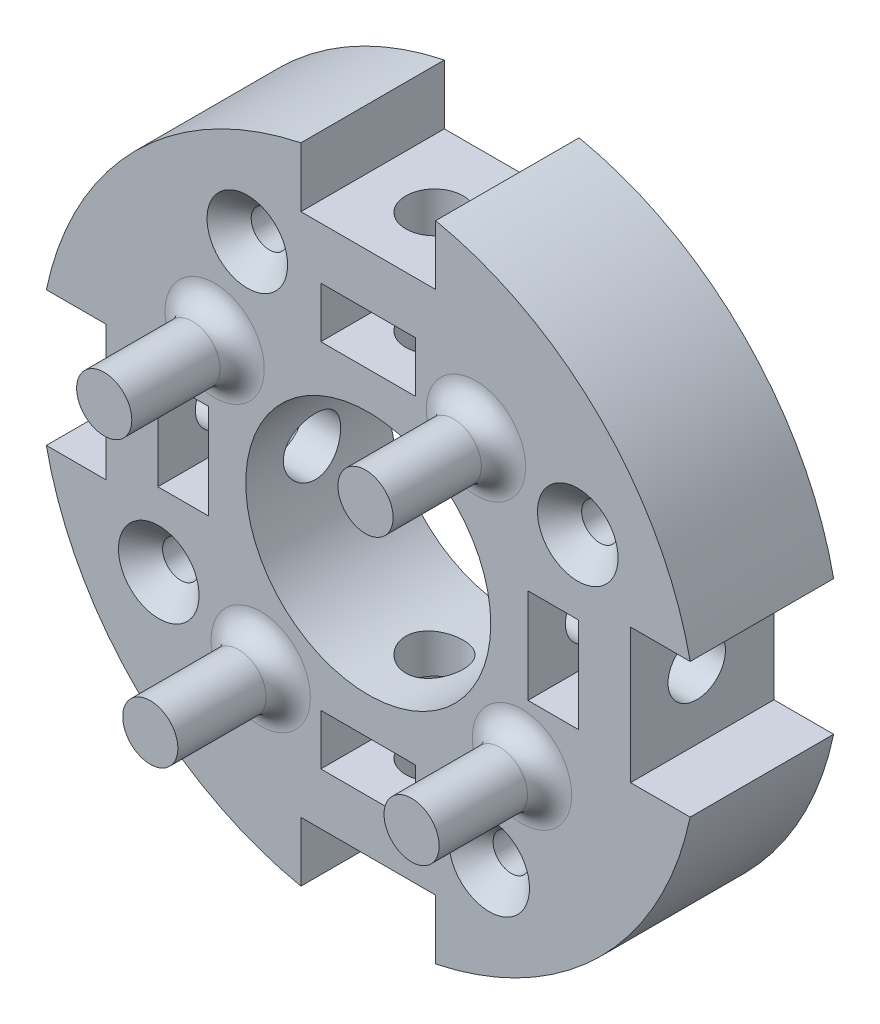
SolidWorks part; units mm, degrees
ref_plane "Plan de face" through (0, 0, 0) normal (0, 0, 1) x (1, 0, 0)
ref_plane "Plan de dessus" through (0, 0, 0) normal (0, 1, 0) x (1, 0, 0)
ref_plane "Plan de droite" through (0, 0, 0) normal (1, 0, 0) x (0, 0, -1)
sketch "Esquisse1" plane through (0, 0, 0) normal (0, 0, 1) x (1, 0, 0)
  line L1 (-29.4129, -5.9059) -> (-23.9629, -5.9059) construction
  line L3 (-29.4129, 5.9059) -> (-23.9629, 5.9059) construction
  line L4 (-23.9629, -5.9059) -> (-23.9629, 5.9059) construction
  line L5 (-29.4129, -5.9059) -> (-23.9629, 5.9059) construction
  line L6 (-29.4129, 5.9059) -> (-23.9629, -5.9059) construction
  line L7 (-5.9059, 29.4129) -> (-5.9059, 23.9629) construction
  line L8 (-5.9059, 23.9629) -> (5.9059, 23.9629) construction
  line L9 (5.9059, 29.4129) -> (5.9059, 23.9629) construction
  line L11 (29.4129, 5.9059) -> (23.9629, 5.9059) construction
  line L12 (23.9629, 5.9059) -> (23.9629, -5.9059) construction
  line L13 (29.4129, -5.9059) -> (23.9629, -5.9059) construction
  line L15 (5.9059, -29.4129) -> (5.9059, -23.9629) construction
  line L16 (5.9059, -23.9629) -> (-5.9059, -23.9629) construction
  line L17 (-5.9059, -29.4129) -> (-5.9059, -23.9629) construction
  line L18 (-6.1059, 29.1677) -> (-6.1059, 23.7629)
  line L19 (-6.1059, 23.7629) -> (6.1059, 23.7629)
  line L20 (6.1059, 29.1677) -> (6.1059, 23.7629)
  line L21 (29.1677, 6.1059) -> (23.7629, 6.1059)
  line L22 (23.7629, 6.1059) -> (23.7629, -6.1059)
  line L23 (29.1677, -6.1059) -> (23.7629, -6.1059)
  line L24 (6.1059, -29.1677) -> (6.1059, -23.7629)
  line L25 (6.1059, -23.7629) -> (-6.1059, -23.7629)
  line L26 (-6.1059, -29.1677) -> (-6.1059, -23.7629)
  line L27 (-29.1677, -6.1059) -> (-23.7629, -6.1059)
  line L28 (-23.7629, -6.1059) -> (-23.7629, 6.1059)
  line L29 (-29.1677, 6.1059) -> (-23.7629, 6.1059)
  line L30 (-4.3, 19.0629) -> (4.3, 19.0629)
  line L31 (-4, 18.7629) -> (4, 18.7629) construction
  line L32 (-4, 18.7629) -> (-4, 14.7629) construction
  line L33 (-4, 14.7629) -> (4, 14.7629) construction
  line L34 (4, 18.7629) -> (4, 14.7629) construction
  line L35 (-4, 18.7629) -> (4, 14.7629) construction
  line L36 (-4, 14.7629) -> (4, 18.7629) construction
  line L37 (4.3, 19.0629) -> (4.3, 14.4629)
  line L38 (-4.3, 14.4629) -> (4.3, 14.4629)
  line L39 (-4.3, 19.0629) -> (-4.3, 14.4629)
  line L40 (19.0629, 4.3) -> (19.0629, -4.3)
  line L41 (19.0629, -4.3) -> (14.4629, -4.3)
  line L42 (14.4629, 4.3) -> (14.4629, -4.3)
  line L43 (19.0629, 4.3) -> (14.4629, 4.3)
  line L44 (4.3, -19.0629) -> (-4.3, -19.0629)
  line L45 (-4.3, -19.0629) -> (-4.3, -14.4629)
  line L46 (4.3, -14.4629) -> (-4.3, -14.4629)
  line L47 (4.3, -19.0629) -> (4.3, -14.4629)
  line L48 (-19.0629, -4.3) -> (-19.0629, 4.3)
  line L49 (-19.0629, 4.3) -> (-14.4629, 4.3)
  line L50 (-14.4629, -4.3) -> (-14.4629, 4.3)
  line L51 (-19.0629, -4.3) -> (-14.4629, -4.3)
  line L52 (-0.2119, 0.3671) -> (-25000.2119, 43301.6373) construction
  line L54 (0, -1000) -> (0, 49000) construction
  arc A0 (-29.4129, -5.9059) -> (-5.9059, -29.4129) centre (0, 0) ccw construction
  circle A1 centre (0, 0) radius 11.1
  circle A2 centre (-10.9602, 18.9835) radius 1.65
  circle A3 centre (18.9835, 10.9602) radius 1.65
  circle A4 centre (10.9602, -18.9835) radius 1.65
  circle A5 centre (-18.9835, -10.9602) radius 1.65
  arc A6 (5.9059, -29.4129) -> (29.4129, -5.9059) centre (0, 0) ccw construction
  arc A7 (29.4129, 5.9059) -> (5.9059, 29.4129) centre (0, 0) ccw construction
  arc A8 (-5.9059, 29.4129) -> (-29.4129, 5.9059) centre (0, 0) ccw construction
  arc A9 (29.1677, 6.1059) -> (6.1059, 29.1677) centre (0, 0) ccw
  arc A10 (6.1059, -29.1677) -> (29.1677, -6.1059) centre (0, 0) ccw
  arc A11 (-29.1677, -6.1059) -> (-6.1059, -29.1677) centre (0, 0) ccw
  arc A12 (-6.1059, 29.1677) -> (-29.1677, 6.1059) centre (0, 0) ccw
  point P4 (-26.6879, 0)
  point P22 (0, 0)
  point P33 (0, 0)
  point P51 (0, 16.7629)
  point P56 (0, 23.7629)
  point P75 (0, 0)
  point P90 (0, 0)
  dimension "D1" = 60
  dimension "D2" = 22.2
  dimension "D7" = 3.3
  dimension "D3" = 5.45
  dimension "D4" = 4
  dimension "D5" = 21.9203
  dimension "D6" = 0.2
  dimension "D9" = 8
  dimension "D10" = 4
  dimension "D11" = 5
  dimension "D16" = 30
  dimension "D12" = 0.3
  dimension "D8" = 4
  dimension "D13" = 4
extrude "Boss.-Extru.1" add sketch "Esquisse1" along normal blind 13
chamfer "Chanfrein1" distance 2 angle 45 4 edges at (-17.3335, -10.9602, 13) (12.6102, -18.9835, 13) (20.6335, 10.9602, 13) (-9.3102, 18.9835, 13)
sketch "Esquisse6" plane through (-23.7629, 0, 0) normal (-1, 0, 0) x (0, 0, 1)
  line L1 (13, -6.1059) -> (13, 6.1059) construction
  circle A0 centre (7, 0) radius 2.6
  dimension "D1" = 5.2
  dimension "D2" = 6
extrude "Enlèv. mat.-Extru.4" cut sketch "Esquisse6" against normal blind 17
pattern_circular "Répétition circulaire1" count 4 over 360 of "Enlèv. mat.-Extru.4"
sketch "Esquisse7" plane through (0, 0, 13) normal (0, 0, 1) x (1, 0, 0)
  line L0 (-1000, 0) -> (49000, 0) construction
  line L1 (0, 0) -> (-40957.6022, 28678.8218) construction
  circle A0 centre (-13.9256, 9.7508) radius 2.5
  circle A1 centre (9.7508, 13.9256) radius 2.5
  circle A2 centre (13.9256, -9.7508) radius 2.5
  circle A3 centre (-9.7508, -13.9256) radius 2.5
  point P16 (0, 0)
  dimension "D3" = 5
  dimension "D1" = 35
  dimension "D2" = 17
extrude "Boss.-Extru.2" add sketch "Esquisse7" along normal blind 10
fillet "Congé1" radius 2 4 edges at (16.4256, -9.7508, 13) (12.2508, 13.9256, 13) (-11.4256, 9.7508, 13) (-7.2508, -13.9256, 13)
